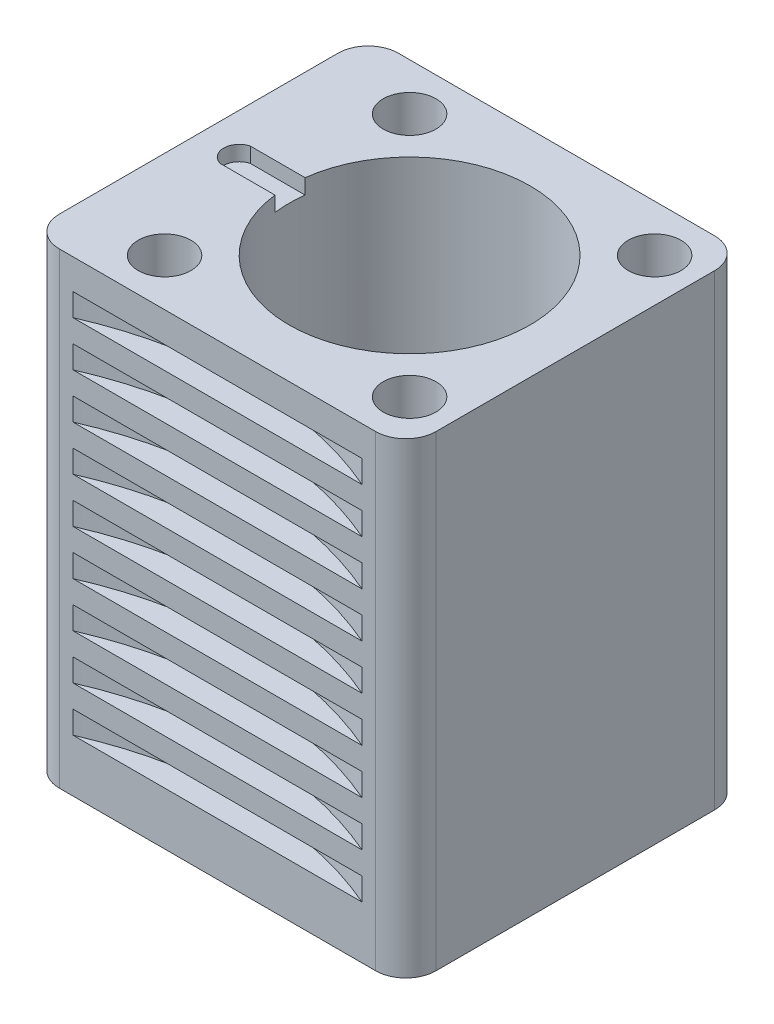
SolidWorks part; units mm, degrees
material "Cast Carbon Steel"
ref_plane "Front Plane" through (0, 0, 0) normal (0, 0, 1) x (1, 0, 0)
ref_plane "Top Plane" through (0, 0, 0) normal (0, 1, 0) x (1, 0, 0)
ref_plane "Right Plane" through (0, 0, 0) normal (1, 0, 0) x (0, 0, -1)
sketch "Sketch1" plane through (0, 0, 0) normal (0, 1, 0) x (1, 0, 0)
  line L1 (-24, -22.5) -> (18, -22.5)
  line L2 (-28, -18.5) -> (-28, 18.5)
  line L3 (-24, 22.5) -> (18, 22.5)
  line L4 (22, -18.5) -> (22, 18.5)
  line L5 (-28, -22.5) -> (22, 22.5) construction
  line L6 (-28, 22.5) -> (22, -22.5) construction
  arc A0 (18, -22.5) -> (22, -18.5) centre (18, -18.5) ccw
  arc A1 (-28, 18.5) -> (-24, 22.5) centre (-24, 18.5) cw
  arc A2 (-24, -22.5) -> (-28, -18.5) centre (-24, -18.5) cw
  arc A3 (18, 22.5) -> (22, 18.5) centre (18, 18.5) cw
  point P0 (-3, 0)
  dimension "D5" = 4
  dimension "D1" = 50
  dimension "D2" = 45
  dimension "D3" = 22
  dimension "D4" = 22.5
extrude "Boss-Extrude1" add sketch "Sketch1" along normal blind 62
sketch "Sketch2" plane through (0, 0, 0) normal (0, -1, 0) x (1, 0, 0)
  circle A0 centre (0, 0) radius 18
  dimension "D1" = 36
extrude "Boss-Extrude2" add sketch "Sketch2" along normal blind 2
sketch "Sketch3" plane through (0, -2, 0) normal (0, -1, 0) x (1, 0, 0)
  circle A0 centre (0, 0) radius 16
  dimension "D1" = 32
extrude "Cut-Extrude1" cut sketch "Sketch3" against normal through all
sketch "Sketch4" plane through (0, 62, 0) normal (0, 1, 0) x (1, 0, 0)
  line L0 (-28, 18.5) -> (-28, -18.5) construction
  line L1 (-23.1445, 2) -> (-8.5852, 2)
  line L3 (-23.1445, -2) -> (-8.5852, -2)
  line L4 (-8.5852, 2) -> (-8.5852, -2)
  arc A0 (-23.1445, 2) -> (-23.1445, -2) centre (-22.61, 0) ccw
  dimension "D1" = 2
  dimension "D2" = 4
  dimension "D3" = 5.39
extrude "Cut-Extrude2" cut sketch "Sketch4" against normal blind 2
sketch "Sketch5" plane through (0, 62, 0) normal (0, 1, 0) x (1, 0, 0)
  line L0 (0, 0) -> (23, 0) construction
  line L1 (0, 0) -> (16.2635, 16.2635) construction
  circle A0 centre (0, 0) radius 23 construction
  circle A1 centre (16.2635, 16.2635) radius 3.5
  circle A2 centre (16.2635, -16.2635) radius 3.5
  circle A3 centre (-16.2635, -16.2635) radius 3.5
  circle A4 centre (-16.2635, 16.2635) radius 3.5
  point P15 (0, 0)
  dimension "D1" = 46
  dimension "D3" = 7
  dimension "D2" = 45
  dimension "D4" = 4
extrude "Cut-Extrude3" cut sketch "Sketch5" against normal through all
ref_plane "Plane1" through (-3, 0, 0) normal (1, 0, 0) x (0, 0, -1)
sketch "Sketch6" plane through (-3, 0, 0) normal (1, 0, 0) x (0, 0, -1)
  line L0 (-22.5, 62) -> (-22.5, 0) construction
  line L1 (-66.5, 58) -> (-18.5, 58)
  line L2 (-66.5, 58) -> (-66.5, 55)
  line L3 (-66.5, 55) -> (-18.5, 55)
  line L4 (-18.5, 58) -> (-18.5, 55)
  line L5 (-18.5, 62) -> (-22.5, 62) construction
  dimension "D1" = 4
  dimension "D2" = 4
  dimension "D3" = 48
  dimension "D4" = 3
revolve "Cut-Revolve1" cut sketch "Sketch6" angle 360 about L2
pattern_linear "LPattern1" count 9 spacing 6 along (0, -1, 0) of "Cut-Revolve1"
mirror "Mirror1" about plane through (0, 0, 0) normal (0, 0, 1) of "LPattern1", "Cut-Revolve1"
sketch "Sketch10" plane through (0, 0, 0) normal (0, 0, 1) x (1, 0, 0)
  line L0 (-24, 62) -> (18, 62) construction
  line L1 (-72, 58) -> (-24, 58)
  line L2 (-72, 58) -> (-72, 55)
  line L3 (-72, 55) -> (-24, 55)
  line L4 (-24, 58) -> (-24, 55)
  line L5 (-28, 62) -> (-28, 0) construction
  dimension "D1" = 4
  dimension "D2" = 4
  dimension "D3" = 3
  dimension "D4" = 48
revolve "Cut-Revolve2" cut sketch "Sketch10" angle 360 about L2
pattern_linear "LPattern2" count 9 spacing 6 along (0, -1, 0) of "Cut-Revolve2"
